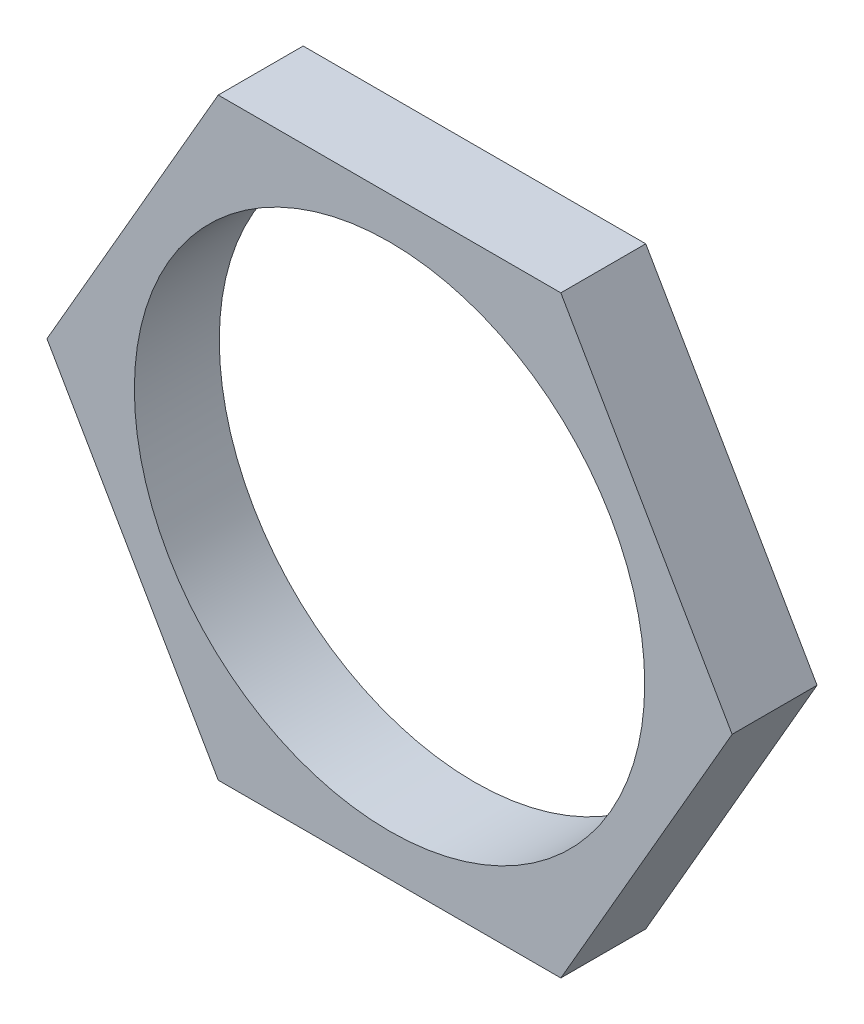
SolidWorks part; units mm, degrees
material "Alloy Steel"
ref_plane "X-Y Datum" through (0, 0, 0) normal (0, 0, 1) x (1, 0, 0)
ref_plane "X-Z Datum" through (0, 0, 0) normal (0, 1, 0) x (1, 0, 0)
ref_plane "Y-Z Datum" through (0, 0, 0) normal (1, 0, 0) x (0, 0, -1)
sketch "Sketch1" plane through (0, 0, 0) normal (0, 0, 1) x (1, 0, 0)
  line L1 (3.9961, -6.9215) -> (7.9923, 0)
  line L2 (7.9923, 0) -> (3.9961, 6.9215)
  line L3 (3.9961, 6.9215) -> (-3.9961, 6.9215)
  line L4 (-3.9961, 6.9215) -> (-7.9923, 0)
  line L5 (-7.9923, 0) -> (-3.9961, -6.9215)
  line L6 (-3.9961, -6.9215) -> (3.9961, -6.9215)
  circle A0 centre (0, 0) radius 6.9215 construction
  circle A1 centre (0, 0) radius 5.9531
  dimension "D2" = 11.9062
  dimension "D1" = 13.843
extrude "Boss-Extrude1" add sketch "Sketch1" along normal mid plane 1.9812
move or copy body "Body-Move/Copy1" [suppressed] bodies to move or copy 101
